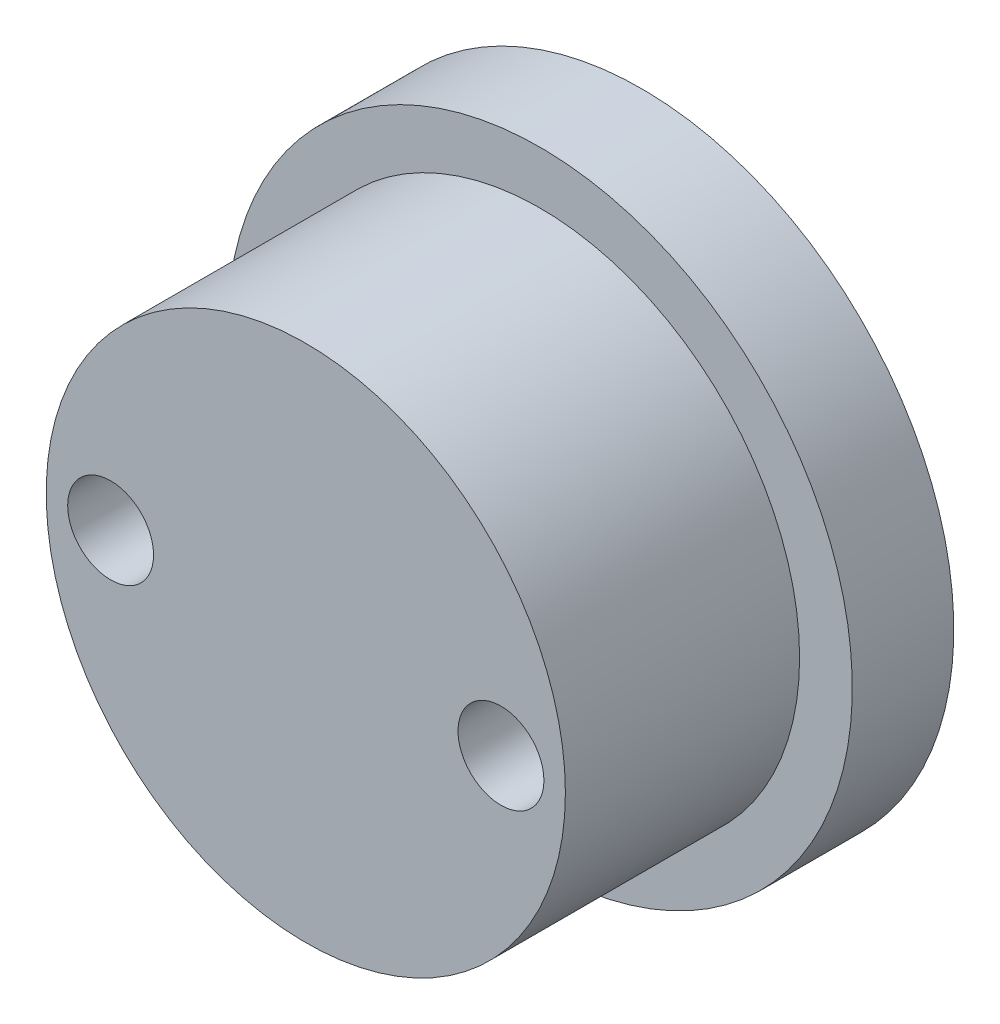
SolidWorks part; units mm, degrees
material "5052-H34"
ref_plane "正面" through (0, 0, 0) normal (0, 0, 1) x (1, 0, 0)
ref_plane "平面" through (0, 0, 0) normal (0, 1, 0) x (1, 0, 0)
ref_plane "右側面" through (0, 0, 0) normal (1, 0, 0) x (0, 0, -1)
sketch "ｽｹｯﾁ1" plane through (0, 0, 0) normal (0, 0, 1) x (1, 0, 0)
  circle A0 centre (0, 0) radius 12
  dimension "D1" = 24
extrude "ﾎﾞｽ - 押し出し1" add sketch "ｽｹｯﾁ1" along normal blind 12.9
sketch "ｽｹｯﾁ2" plane through (0, 0, 12.9) normal (0, 0, 1) x (1, 0, 0)
  circle A0 centre (0, 0) radius 9.975
  circle A1 centre (0, 0) radius 12
  circle A2 centre (0, 0) radius 12 construction
  dimension "D1" = 19.95
extrude "ｶｯﾄ - 押し出し1" cut sketch "ｽｹｯﾁ2" against normal blind 9
sketch "ｽｹｯﾁ3" plane through (0, 0, 0) normal (0, 0, -1) x (-1, 0, 0)
  line L0 (0, 7.5) -> (0, 0) construction
  circle A0 centre (0, 0) radius 7.5 construction
  circle A1 centre (7.5, 0) radius 1.65
  circle A2 centre (-7.5, 0) radius 1.65
  dimension "D1" = 15
  dimension "D2" = 3.3
extrude "ｶｯﾄ - 押し出し2" cut sketch "ｽｹｯﾁ3" against normal up to surface (12.9 mm away) up to face at (9.975, 0, 12.9)
